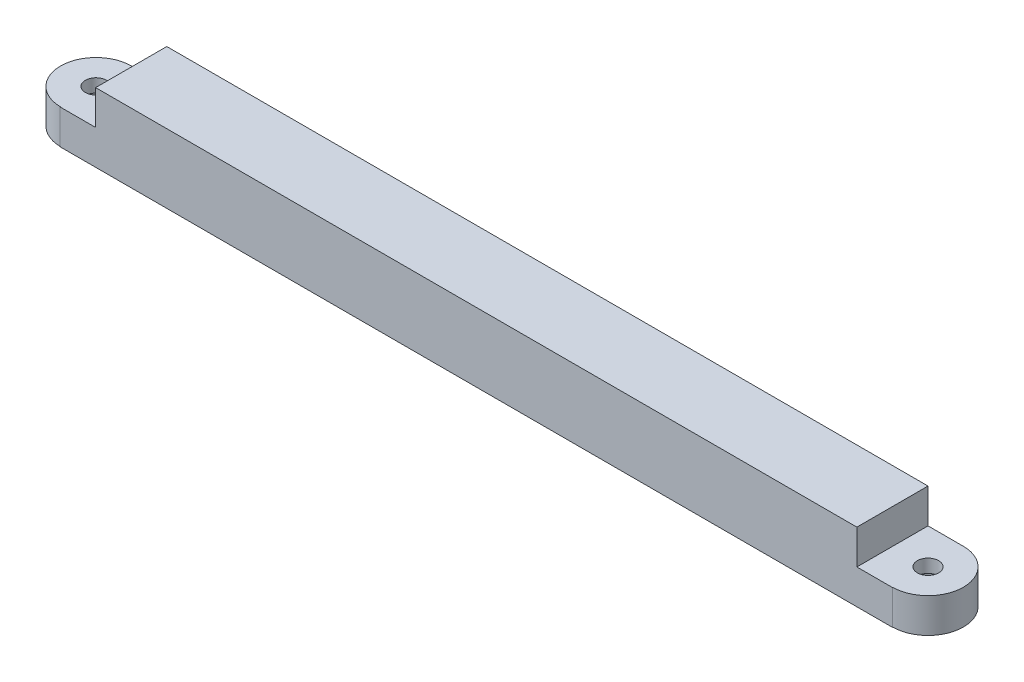
SolidWorks part; units mm, degrees
material "ABS"
ref_plane "Front Plane" through (0, 0, 0) normal (0, 0, 1) x (1, 0, 0)
ref_plane "Top Plane" through (0, 0, 0) normal (0, 1, 0) x (1, 0, 0)
ref_plane "Right Plane" through (0, 0, 0) normal (1, 0, 0) x (0, 0, -1)
sketch "Sketch1" plane through (0, 0, 0) normal (0, 1, 0) x (1, 0, 0)
  line L0 (0, 0) -> (58.75, 0)
  line L1 (0, 0) -> (0, 5)
  line L2 (58.75, -5.049) -> (0, -5.049)
  line L3 (58.75, -5.049) -> (58.75, 5)
  line L4 (0, -5.049) -> (0, 5)
  line L5 (58.75, 5) -> (0, 5)
  line L6 (58.75, -5.049) -> (0, 5) construction
  line L7 (0, -5.049) -> (58.75, 5) construction
  circle A0 centre (58.75, 0) radius 1.5
  circle A1 centre (58.75, 0) radius 5
  point P5 (29.375, -0.0245)
  dimension "D3" = 3
  dimension "D1" = 58.75
  dimension "D2" = 5
extrude "Boss-Extrude1" add sketch "Sketch1" along normal blind 9.75 contours A1 L5 L1 L0 | A1 L0 L4 L2 L3 | L3 A1 A0 | L3 A1 L0 A0 | L0 A1 L3 A0
mirror "Mirror1" about plane through (0, 0, 0) normal (1, 0, 0) of "Boss-Extrude1"
sketch "Sketch2" plane through (0, 9.75, 0) normal (0, 1, 0) x (1, 0, 0)
  line L0 (63.75, 0) -> (53.75, 0)
  line L2 (53.75, 0) -> (53.75, 5)
  line L4 (58.75, 5) -> (-58.75, 5) construction
  line L5 (53.75, 5) -> (58.75, 5)
  line L6 (53.75, 0) -> (53.75, -5.049)
  line L7 (58.75, -5.049) -> (-58.75, -5.049) construction
  line L8 (53.75, -5.049) -> (58.75, -5.049)
  arc A1 (58.75, -5) -> (58.75, 5) centre (58.75, 0) ccw construction
  arc A2 (58.75, 5) -> (63.75, 0) centre (58.75, 0) cw
  arc A3 (58.75, -5.049) -> (63.75, 0) centre (58.7007, 0) ccw
  circle M1 centre (58.75, 0) radius 1.5
  line M2 (58.75, -5.049) -> (58.75, -5)
  arc M3 (58.75, -5) -> (58.75, 5) centre (58.75, 0) ccw
  line M4 (58.75, 5) -> (-58.75, 5)
  line M7 (-58.75, -5.049) -> (58.75, -5.049)
  dimension "D1" = 10
extrude "Cut-Extrude3" cut sketch "Sketch2" against normal blind 4.875 contours L2 L0 M1 M3 M4 | L0 L6 M7 M2 M3 M1
mirror "Mirror2" about plane through (0, 0, 0) normal (1, 0, 0) of "Cut-Extrude3"
sketch "Sketch3" plane through (0, 0, 0) normal (0, -1, 0) x (-1, 0, 0)
  circle A0 centre (58.75, 0) radius 2.825
  circle A1 centre (-58.75, 0) radius 2.825
  dimension "D1" = 5.65
  dimension "D2" = 5.65
extrude "Cut-Extrude4" cut sketch "Sketch3" against normal blind 3
